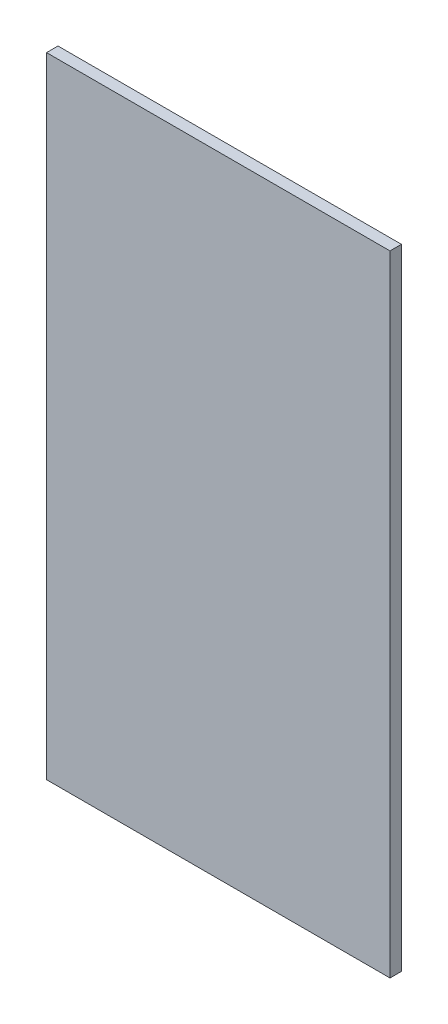
SolidWorks part; units mm, degrees
material "Pino"
ref_plane "Alzado" through (0, 0, 0) normal (0, 0, 1) x (1, 0, 0)
ref_plane "Planta" through (0, 0, 0) normal (0, 1, 0) x (1, 0, 0)
ref_plane "Vista lateral" through (0, 0, 0) normal (1, 0, 0) x (0, 0, -1)
sketch "Croquis2" plane through (0, 0, 0) normal (0, 0, 1) x (1, 0, 0)
  line L1 (0, 0) -> (300, 0)
  line L2 (0, 0) -> (0, 550)
  line L3 (0, 550) -> (300, 550)
  line L4 (300, 0) -> (300, 550)
  dimension "D1" = 550
  dimension "D2" = 300
extrude "Saliente-Extruir1" add sketch "Croquis2" along normal blind 10
